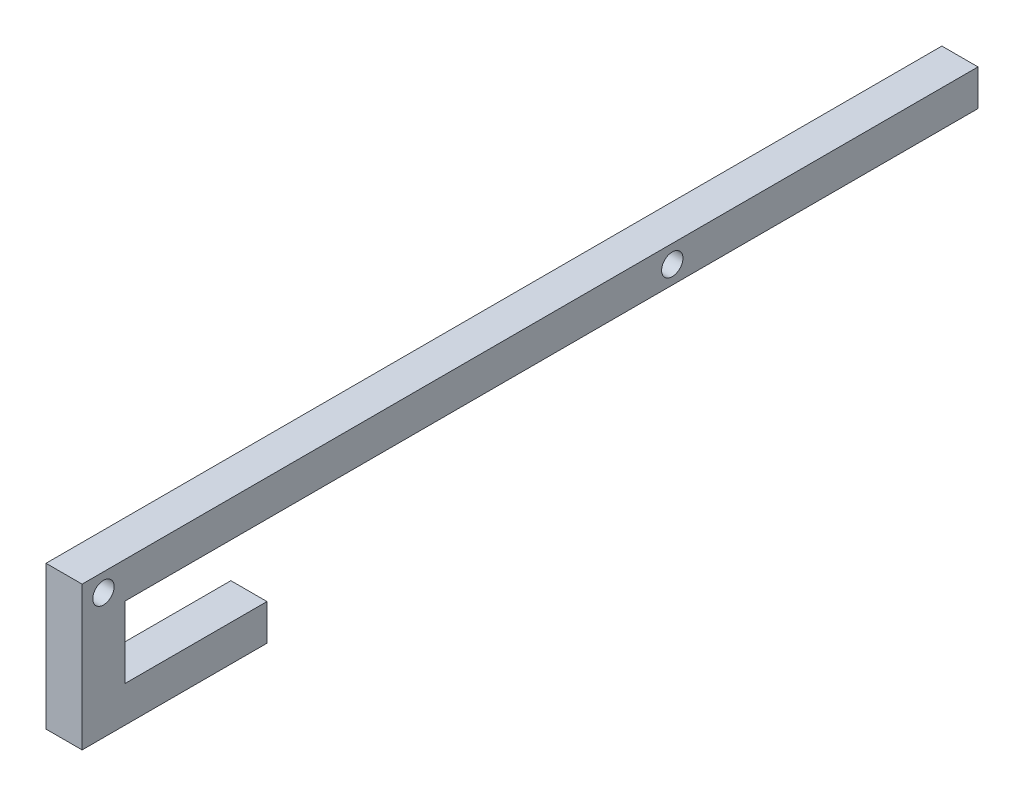
SolidWorks part; units mm, degrees
ref_plane "Front Plane" through (0, 0, 0) normal (0, 0, 1) x (1, 0, 0)
ref_plane "Top Plane" through (0, 0, 0) normal (0, 1, 0) x (1, 0, 0)
ref_plane "Right Plane" through (0, 0, 0) normal (1, 0, 0) x (0, 0, -1)
sketch "Sketch1" plane through (0, 0, 0) normal (1, 0, 0) x (0, 0, -1)
  line L0 (7.5, -37.8) -> (7.5, 12.7) construction
  line L1 (0, 0) -> (315, 0)
  line L2 (0, 0) -> (0, 12.7)
  line L3 (0, 12.7) -> (315, 12.7)
  line L4 (315, 0) -> (315, 12.7)
  line L5 (0, 0) -> (15, 0)
  line L6 (0, 0) -> (0, -37.8)
  line L7 (0, -37.8) -> (15, -37.8)
  line L8 (15, 0) -> (15, -37.8)
  line L9 (15, -37.8) -> (65, -37.8)
  line L10 (15, -37.8) -> (15, -25.1)
  line L11 (15, -25.1) -> (65, -25.1)
  line L12 (65, -37.8) -> (65, -25.1)
  line L13 (307.5, 12.7) -> (307.5, 0) construction
  point P15 (315, 6.35)
  dimension "D1" = 25.1
  dimension "D2" = 7.5
  dimension "D3" = 15
  dimension "D4" = 12.7
  dimension "D5" = 12.7
  dimension "D6" = 50
  dimension "D7" = 300
extrude "Boss-Extrude1" add sketch "Sketch1" along normal blind 12.7 contours L1 L4 L3 L2 | L8 L1 L6 L7 | L9 L12 L11 L8
sketch "Sketch2" plane through (12.7, 0, 0) normal (1, 0, 0) x (0, 0, -1)
  line L0 (157.5, 12.7) -> (157.5, 0) construction
  line L1 (0, 12.7) -> (315, 12.7) construction
  line L2 (15, 0) -> (315, 0) construction
  line L3 (0, -37.8) -> (0, 12.7) construction
  circle A0 centre (7.5, 6.35) radius 3.75
  circle A1 centre (207.5, 6.35) radius 3.75
  point P4 (157.5, 6.35)
  point P11 (0, 0)
  point P12 (157.5, 12.7)
  point P15 (0, 0)
  dimension "D3" = 7.5
  dimension "D1" = 200
  dimension "D2" = 7.5
extrude "Cut-Extrude1" cut sketch "Sketch2" against normal through all
